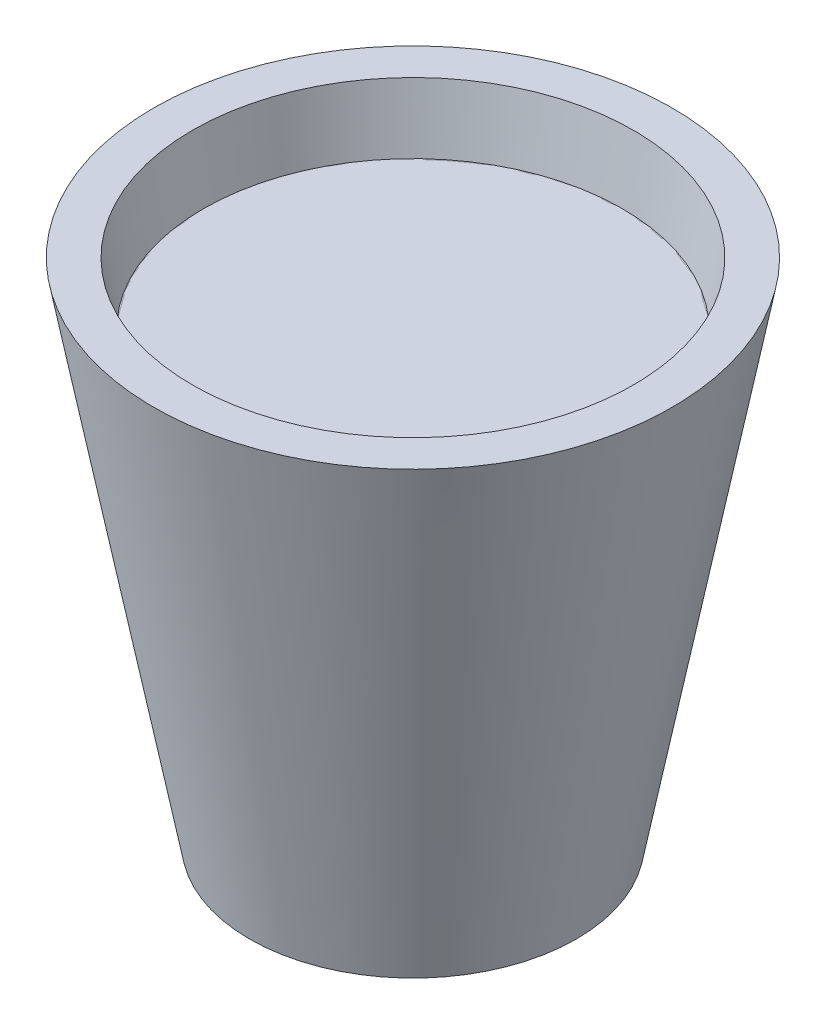
SolidWorks part; units mm, degrees
ref_plane "Front Plane" through (0, 0, 0) normal (0, 0, 1) x (1, 0, 0)
ref_plane "Top Plane" through (0, 0, 0) normal (0, 1, 0) x (1, 0, 0)
ref_plane "Right Plane" through (0, 0, 0) normal (1, 0, 0) x (0, 0, -1)
sketch "Sketch1" plane through (0, 0, 0) normal (0, 0, 1) x (1, 0, 0)
  line L0 (0, 0) -> (28.575, 0)
  line L1 (28.575, 0) -> (45.3307, 88.9)
  line L4 (45.3307, 88.9) -> (38.5677, 88.9)
  line L5 (38.5677, 88.9) -> (22.8892, 8.3289)
  line L6 (22.8892, 8.3289) -> (0, 8.3289)
  line L7 (0, 8.3289) -> (0, 0)
  dimension "D1" = 28.575
revolve "Revolve2" add sketch "Sketch1" angle 360 about L7
sketch "Sketch3" plane through (0, 88.9, 0) normal (0, 1, 0) x (1, 0, 0)
  circle A0 centre (0, 0) radius 38.5677
extrude "Boss-Extrude2" add sketch "Sketch3" against normal blind 81.026 draft 10 separate body
sketch "Sketch5" plane through (0, 88.9, 0) normal (0, 1, 0) x (1, 0, 0)
  circle A0 centre (0, 0) radius 38.5677
extrude "Cut-Extrude3" cut sketch "Sketch5" against normal blind 10.922 draft 10
